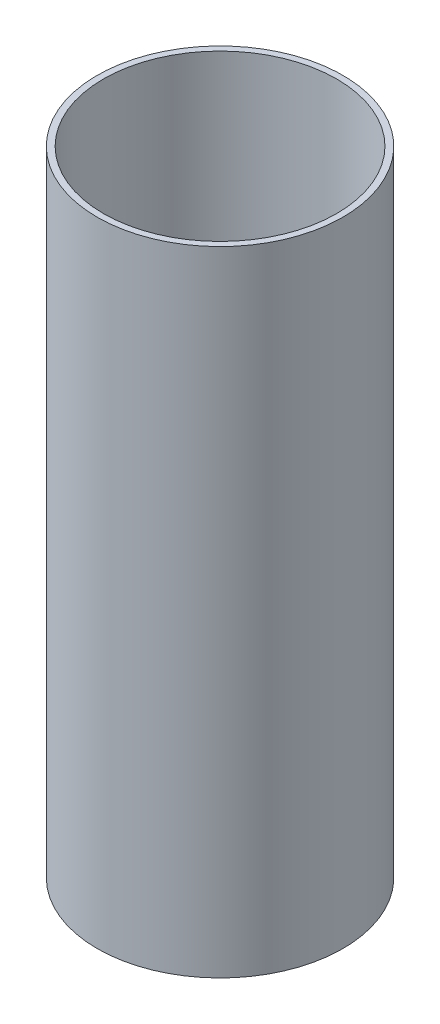
SolidWorks part; units mm, degrees
material "PVC Rigid"
ref_plane "Front Plane" through (0, 0, 0) normal (0, 0, 1) x (1, 0, 0)
ref_plane "Top Plane" through (0, 0, 0) normal (0, 1, 0) x (1, 0, 0)
ref_plane "Right Plane" through (0, 0, 0) normal (1, 0, 0) x (0, 0, -1)
sketch "Sketch1" plane through (0, 0, 0) normal (0, 1, 0) x (1, 0, 0)
  circle A0 centre (0, 0) radius 93.6625
  circle A1 centre (0, 0) radius 88.9
  dimension "D1" = 187.325
  dimension "D2" = 177.8
extrude "Boss-Extrude1" add sketch "Sketch1" along normal mid plane 482.854
ref_plane "Plane1" through (0, 0, 93.6625) normal (0, 0, 1) x (1, 0, 0)
sketch "Sketch3" plane through (0, 0, 93.6625) normal (0, 0, 1) x (1, 0, 0)
  line L0 (0, -55) -> (0, 55) construction
  line L1 (-93.6625, -241.427) -> (93.6625, -241.427) construction
  circle A0 centre (0, -235.077) radius 1.4351
  dimension "D1" = 2.8702
  dimension "D2" = 6.35
extrude "Cut-Extrude1" [suppressed] cut sketch "Sketch3" against normal blind 19.304
pattern_circular "CirPattern1" [suppressed] count 12 over 360
mirror "Mirror1" [suppressed] about plane through (0, 0, 0) normal (0, 1, 0)
sketch "Sketch4" [suppressed] plane through (0, 0, 93.6625) normal (0, 0, 1) x (1, 0, 0)
  line L0 (0, -103.0288) -> (0, 103.0288) construction
  circle A0 centre (0, -78.359) radius 1.4351
  circle A1 centre (0, 78.359) radius 1.4351
  circle A2 centre (0, 235.077) radius 1.4351 construction
  circle A3 centre (0, -235.077) radius 1.4351 construction
  dimension "D1" = 2.8702
  dimension "D2" = 2.8702
  dimension "D3" = 156.718
  dimension "D4" = 156.718
extrude "Cut-Extrude2" [suppressed] cut sketch "Sketch4" against normal blind 25.146
pattern_circular "CirPattern2" [suppressed] count 3 over 360
